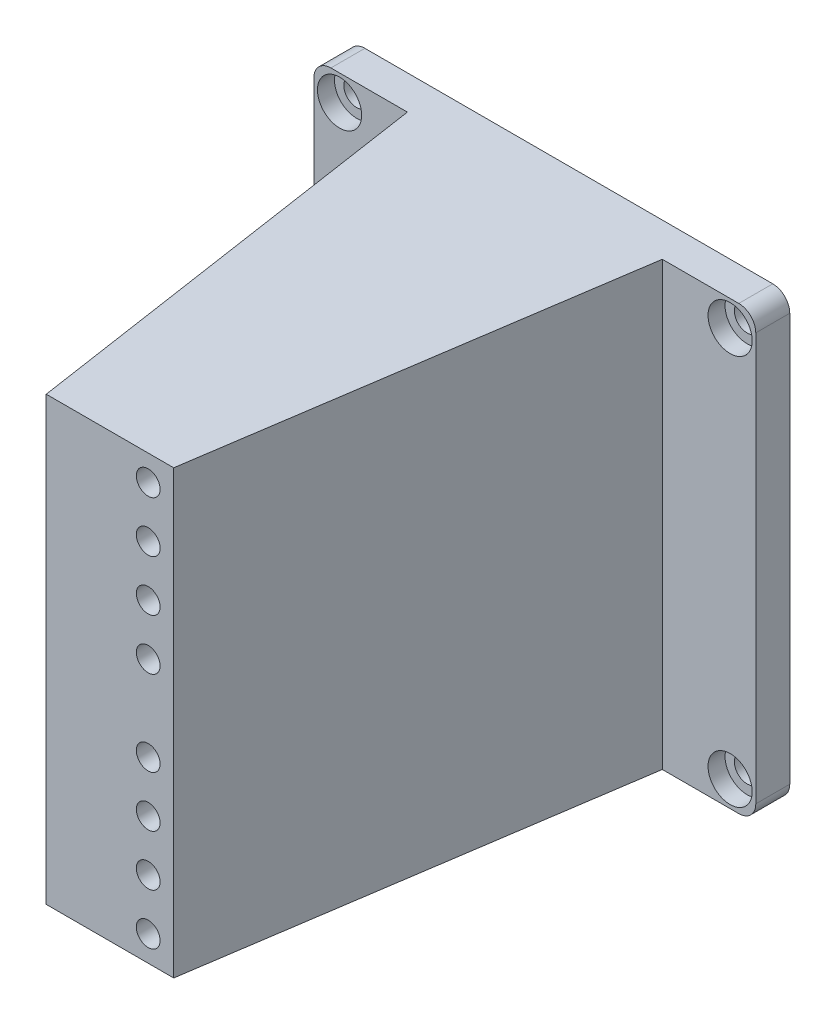
SolidWorks part; units mm, degrees
ref_plane "Front Plane" through (0, 0, 0) normal (0, 0, 1) x (1, 0, 0)
ref_plane "Top Plane" through (0, 0, 0) normal (0, 1, 0) x (1, 0, 0)
ref_plane "Right Plane" through (0, 0, 0) normal (1, 0, 0) x (0, 0, -1)
sketch "Sketch1" plane through (0, 0, 0) normal (0, 0, 1) x (1, 0, 0)
  line L1 (0, 0) -> (52, 0)
  line L2 (0, 0) -> (0, 52)
  line L3 (0, 52) -> (52, 52)
  line L4 (52, 0) -> (52, 52)
  line L5 (0, 17.5) -> (0, 32.5)
  line L6 (0, 32.5) -> (52, 32.5)
  line L7 (52, 32.5) -> (52, 17.5)
  line L8 (0, 17.5) -> (52, 17.5)
  line L9 (0, 26) -> (52, 26)
  line L10 (24.7003, 52) -> (26, 52)
  line L11 (26, 52) -> (26, 0)
  circle A0 centre (49, 49) radius 1.5
  circle A1 centre (3, 49) radius 1.5
  circle A2 centre (3, 3) radius 1.5
  circle A3 centre (49, 3) radius 1.5
  dimension "D3" = 3
  dimension "D1" = 52
  dimension "D2" = 52
  dimension "D4" = 46
  dimension "D5" = 46
extrude "Boss-Extrude1" add sketch "Sketch1" against normal blind 4 contours L4 L3 L2 L1
ref_plane "Plane3" through (0, 52, 0) normal (0, 1, 0) x (1, 0, 0)
sketch "Sketch4" plane through (0, 52, 0) normal (0, 1, 0) x (1, 0, 0)
  line L0 (26, 0) -> (26, -50)
  line L2 (0, 0) -> (52, 0) construction
  line L4 (11, 0) -> (41, 0)
  line L5 (33.5, -50) -> (18.5, -50)
  line L6 (11, 0) -> (18.5, -50)
  line L7 (41, 0) -> (33.5, -50)
  dimension "D1" = 50
  dimension "D2" = 15
  dimension "D3" = 7.5
extrude "Boss-Extrude2" add sketch "Sketch4" against normal blind 52 contours L7 L5 L6 L4
ref_plane "Plane4" through (0, 0, 50) normal (0, 0, 1) x (1, 0, 0)
sketch "Sketch5" plane through (0, 0, 50) normal (0, 0, 1) x (1, 0, 0)
  line L1 (33.5, 52) -> (18.5, 52) construction
  line L3 (18.5, 26) -> (33.5, 26)
  line L4 (18.5, 0) -> (18.5, 52) construction
  line L5 (33.5, 0) -> (33.5, 52) construction
  circle A0 centre (30.5, 49) radius 1.4
  circle A1 centre (30.5, 43) radius 1.4
  circle A2 centre (30.5, 37) radius 1.4
  circle A3 centre (30.5, 31) radius 1.4
  circle A4 centre (30.5, 21) radius 1.4
  circle A5 centre (30.5, 15) radius 1.4
  circle A6 centre (30.5, 9) radius 1.4
  circle A7 centre (30.5, 3) radius 1.4
  point P0 (0, 0)
  dimension "D1" = 2.8
  dimension "D2" = 3
  dimension "D3" = 6
  dimension "D4" = 6
  dimension "D5" = 6
  dimension "D6" = 3
extrude "Cut-Extrude4" cut sketch "Sketch5" against normal blind 6 contours A6 | A7 | A5 | A4 | A3 | A2 | A1 | A0
sketch "Sketch6" plane through (0, 0, 0) normal (0, 0, 1) x (1, 0, 0)
  line L0 (26, 52) -> (26, 0)
  line L1 (0, 52) -> (52, 52) construction
  line L2 (0, 0) -> (52, 0) construction
  line L3 (52, 26) -> (0, 26)
  line L4 (52, 0) -> (52, 52) construction
  line L5 (0, 0) -> (0, 52) construction
  circle A0 centre (26, 26) radius 32.5
  circle A1 centre (26, 58.5) radius 1.5
  circle A6 centre (26, -6.5) radius 1.5
  circle A11 centre (6.897, 52.2931) radius 1.5 [skipped]
  circle A12 centre (-4.9093, 36.0431) radius 1.5 [skipped]
  circle A13 centre (-4.9093, 15.9569) radius 1.5 [skipped]
  circle A14 centre (6.897, -0.2931) radius 1.5 [skipped]
  circle A15 centre (45.103, -0.2931) radius 1.5 [skipped]
  circle A16 centre (56.9093, 15.9569) radius 1.5 [skipped]
  circle A17 centre (56.9093, 36.0431) radius 1.5 [skipped]
  circle A18 centre (45.103, 52.2931) radius 1.5 [skipped]
  circle A19 centre (48.981, 48.981) radius 1.5
  circle A20 centre (58.5, 26) radius 1.5
  circle A21 centre (48.981, 3.019) radius 1.5
  circle A22 centre (26, -6.5) radius 1.5
  circle A23 centre (3.019, 3.019) radius 1.5
  circle A24 centre (-6.5, 26) radius 1.5
  circle A25 centre (3.019, 48.981) radius 1.5
  point P35 (26, 26)
  point P37 (26, 26)
  dimension "D1" = 65
  dimension "D2" = 10
  dimension "D3" = 8
extrude "Cut-Extrude5" cut sketch "Sketch6" against normal blind 6 contours A25 | A19 | A21 | A23
sketch "Sketch7" plane through (0, 0, 0) normal (0, 0, 1) x (1, 0, 0)
  circle A0 centre (48.981, 48.981) radius 2.6
  circle A1 centre (3.019, 48.981) radius 2.6
  circle A2 centre (3.019, 3.019) radius 2.6
  circle A3 centre (48.981, 3.019) radius 2.6
extrude "Cut-Extrude6" cut sketch "Sketch7" against normal blind 2
fillet "Fillet1" radius 2 4 edges at (52, 0, -2) (0, 0, -2) (0, 52, -2) (52, 52, -2)
